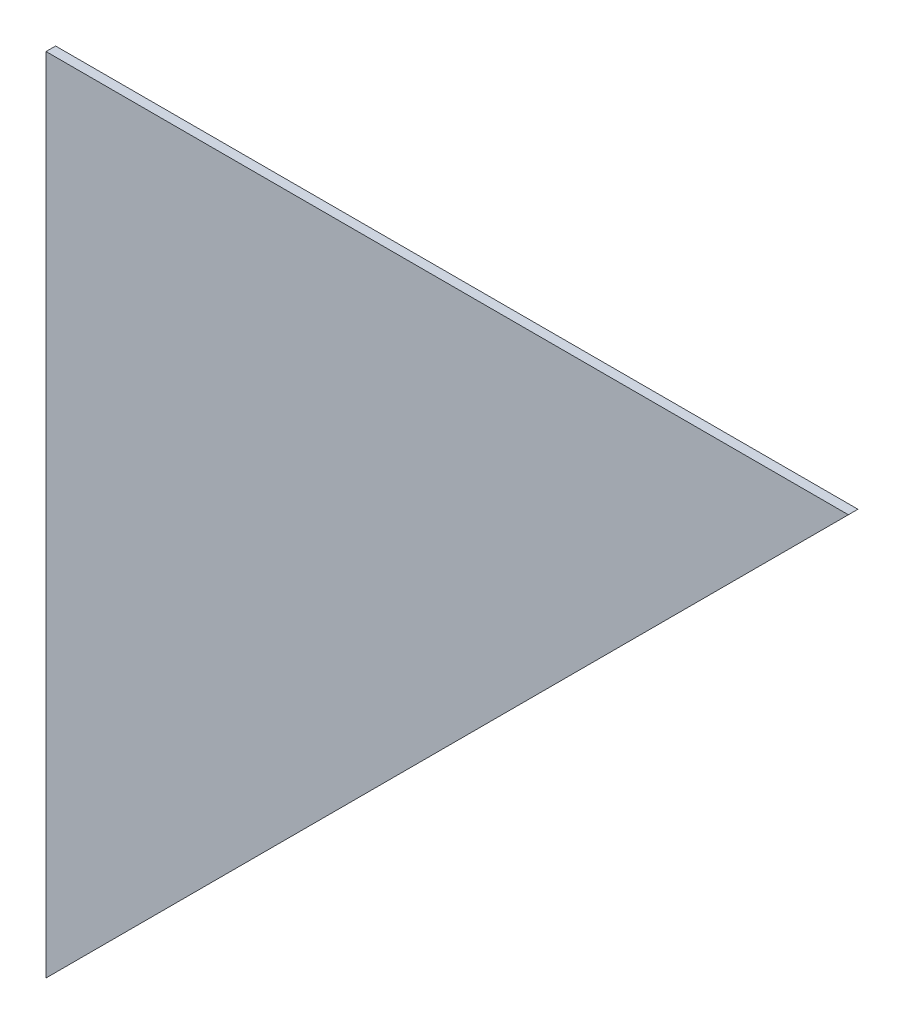
SolidWorks part; units mm, degrees
material "Si External Bypass Diode"
ref_plane "Front Plane" through (0, 0, 0) normal (0, 0, 1) x (1, 0, 0)
ref_plane "Top Plane" through (0, 0, 0) normal (0, 1, 0) x (1, 0, 0)
ref_plane "Right Plane" through (0, 0, 0) normal (1, 0, 0) x (0, 0, -1)
sketch "Sketch2" plane through (0, 0, 0) normal (0, 0, 1) x (1, 0, 0)
  line L0 (-9.1519, 19.5568) -> (1.7481, 19.5568)
  line L1 (1.7481, 19.5568) -> (-9.1519, 8.6568)
  line L2 (-9.1519, 8.6568) -> (-9.1519, 19.5568)
extrude "Boss-Extrude1" add sketch "Sketch2" along normal blind 0.13
